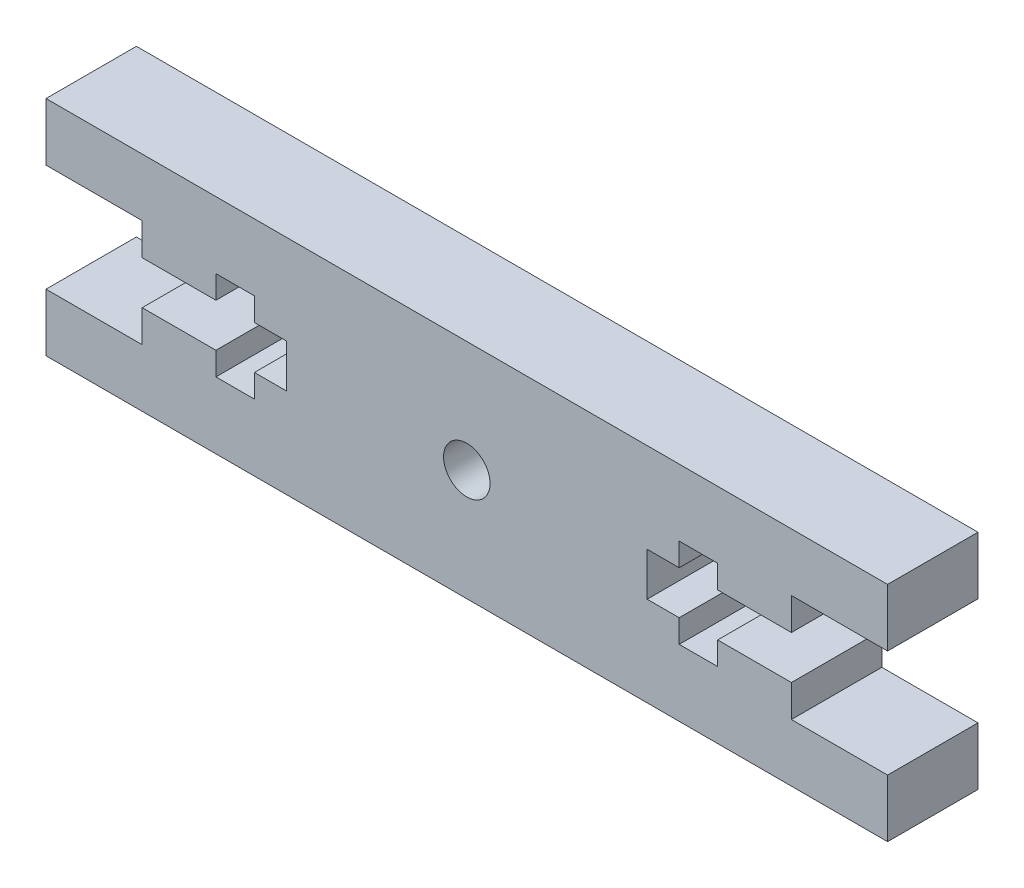
SolidWorks part; units mm, degrees
material "Acrylic (Medium-high impact)"
ref_plane "Front Plane" through (0, 0, 0) normal (0, 0, 1) x (1, 0, 0)
ref_plane "Top Plane" through (0, 0, 0) normal (0, 1, 0) x (1, 0, 0)
ref_plane "Right Plane" through (0, 0, 0) normal (1, 0, 0) x (0, 0, -1)
sketch "Sketch1" plane through (0, 0, 0) normal (0, 0, 1) x (1, 0, 0)
  line L0 (727.3394, 352.6063) -> (779.8394, 352.6063)
  line L1 (753.5894, -654.3154) -> (753.5894, 49345.6846) construction
  line L2 (742.3394, 347.0063) -> (742.3394, 344.3063)
  line L3 (727.3394, 349.0063) -> (733.3394, 349.0063)
  line L4 (733.3394, 349.0063) -> (733.3394, 347.0063)
  line L5 (733.3394, 347.0063) -> (737.9394, 347.0063)
  line L6 (737.9394, 348.4463) -> (740.3394, 348.4463)
  line L7 (-245.8122, 345.6563) -> (49754.1878, 345.6563) construction
  line L8 (727.3394, 338.7063) -> (727.3394, 342.3063)
  line L9 (737.9394, 344.3063) -> (737.9394, 342.8663)
  line L10 (740.3394, 342.8663) -> (740.3394, 344.3063)
  line L11 (740.3394, 344.3063) -> (742.3394, 344.3063)
  line L12 (737.9394, 342.8663) -> (740.3394, 342.8663)
  line L13 (733.3394, 344.3063) -> (737.9394, 344.3063)
  line L14 (740.3394, 347.0063) -> (742.3394, 347.0063)
  line L15 (740.3394, 348.4463) -> (740.3394, 347.0063)
  line L16 (733.3394, 342.3063) -> (733.3394, 344.3063)
  line L17 (737.9394, 347.0063) -> (737.9394, 348.4463)
  line L18 (727.3394, 342.3063) -> (733.3394, 342.3063)
  line L19 (727.3394, 338.7063) -> (779.8394, 338.7063)
  line L20 (779.8394, 352.6063) -> (779.8394, 349.0063)
  line L21 (779.8394, 342.3063) -> (773.8394, 342.3063)
  line L22 (769.2394, 347.0063) -> (769.2394, 348.4463)
  line L23 (773.8394, 342.3063) -> (773.8394, 344.3063)
  line L24 (766.8394, 348.4463) -> (766.8394, 347.0063)
  line L25 (766.8394, 347.0063) -> (764.8394, 347.0063)
  line L26 (773.8394, 344.3063) -> (769.2394, 344.3063)
  line L27 (769.2394, 342.8663) -> (766.8394, 342.8663)
  line L28 (766.8394, 344.3063) -> (764.8394, 344.3063)
  line L29 (766.8394, 342.8663) -> (766.8394, 344.3063)
  line L30 (769.2394, 344.3063) -> (769.2394, 342.8663)
  line L31 (779.8394, 338.7063) -> (779.8394, 342.3063)
  line L32 (769.2394, 348.4463) -> (766.8394, 348.4463)
  line L33 (773.8394, 347.0063) -> (769.2394, 347.0063)
  line L34 (727.3394, 352.6063) -> (727.3394, 349.0063)
  line L35 (773.8394, 349.0063) -> (773.8394, 347.0063)
  line L36 (779.8394, 349.0063) -> (773.8394, 349.0063)
  line L37 (764.8394, 347.0063) -> (764.8394, 344.3063)
  circle A0 centre (753.5894, 345.6563) radius 1.45
  point P7 (753.5894, 352.6063)
  point P8 (764.8394, 345.6563)
  point P24 (742.3394, 345.6563)
  point P28 (753.5894, 338.7063)
  point P46 (753.5894, 352.6063)
  dimension "D1" = 3.6
  dimension "D2" = 4.6
  dimension "D3" = 6
  dimension "D4" = 1.44
  dimension "D5" = 2.4
  dimension "D6" = 2
  dimension "D7" = 2
  dimension "D8" = 40.5
  dimension "D9" = 2.7
extrude "Boss-Extrude2" add sketch "Sketch1" along normal blind 5.64
